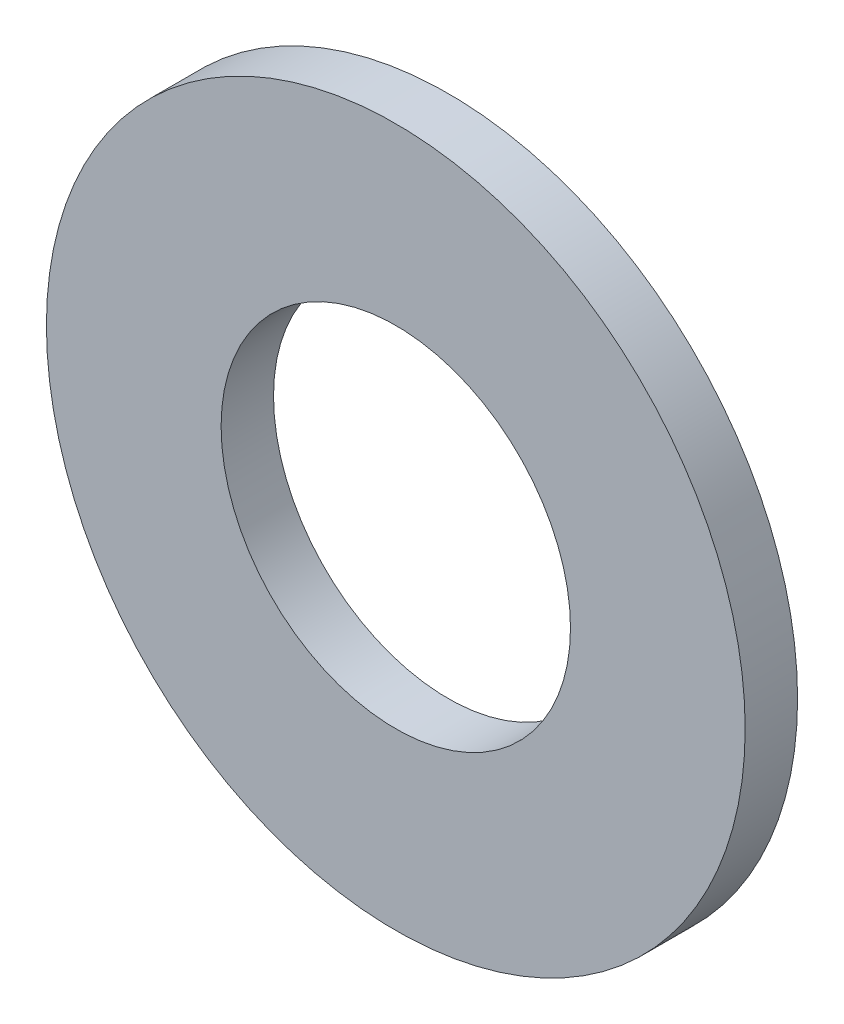
SolidWorks part; units mm, degrees
ref_plane "前视基准面" through (0, 0, 0) normal (0, 0, 1) x (1, 0, 0)
ref_plane "上视基准面" through (0, 0, 0) normal (0, 1, 0) x (1, 0, 0)
ref_plane "右视基准面" through (0, 0, 0) normal (1, 0, 0) x (0, 0, -1)
sketch "草图1" plane through (0, 0, 0) normal (0, 0, 1) x (1, 0, 0)
  circle A0 centre (0, 0) radius 1
  circle A1 centre (0, 0) radius 2
  dimension "D1" = 4
  dimension "D2" = 2
extrude "凸台-拉伸1" add sketch "草图1" along normal mid plane 0.3
